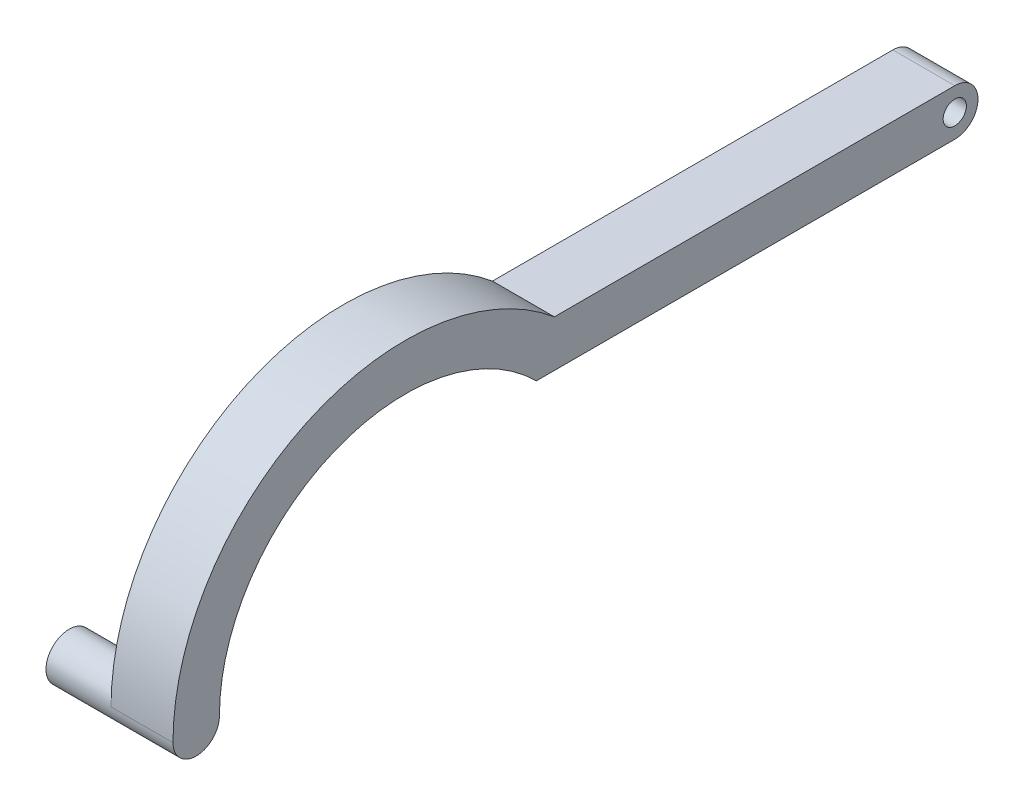
SolidWorks part; units mm, degrees
ref_plane "Front Plane" through (0, 0, 0) normal (0, 0, 1) x (1, 0, 0)
ref_plane "Top Plane" through (0, 0, 0) normal (0, 1, 0) x (1, 0, 0)
ref_plane "Right Plane" through (0, 0, 0) normal (1, 0, 0) x (0, 0, -1)
sketch "Sketch1" plane through (0, 0, 0) normal (1, 0, 0) x (0, 0, -1)
  line L0 (0, 0) -> (48.9898, 10) construction
  line L2 (48.9898, 11.5) -> (23.1307, 11.5)
  line L4 (48.9898, 8.5) -> (21.9705, 8.5)
  arc A0 (-1.5, 0) -> (1.5, 0) centre (0, 0) ccw
  arc A1 (48.9898, 8.5) -> (48.9898, 11.5) centre (48.9898, 10) ccw
  arc A2 (1.5, 0) -> (21.9705, 8.5) centre (13.5, 0) cw
  arc A3 (23.1307, 11.5) -> (-1.5, 0) centre (13.5, 0) ccw
  circle A4 centre (0, 0) radius 1.625 construction
  circle A5 centre (48.9898, 10) radius 0.75
  dimension "D1" = 50
  dimension "D2" = 3
  dimension "D5" = 3.25
  dimension "D6" = 1.5
  dimension "D4" = 12
  dimension "D3" = 10
extrude "Boss-Extrude1" add sketch "Sketch1" along normal blind 4
sketch "Sketch2" plane through (0, 0, 0) normal (-1, 0, 0) x (0, 0, 1)
  circle A0 centre (0, 0) radius 1.5
extrude "Boss-Extrude2" add sketch "Sketch2" along normal blind 4.2
